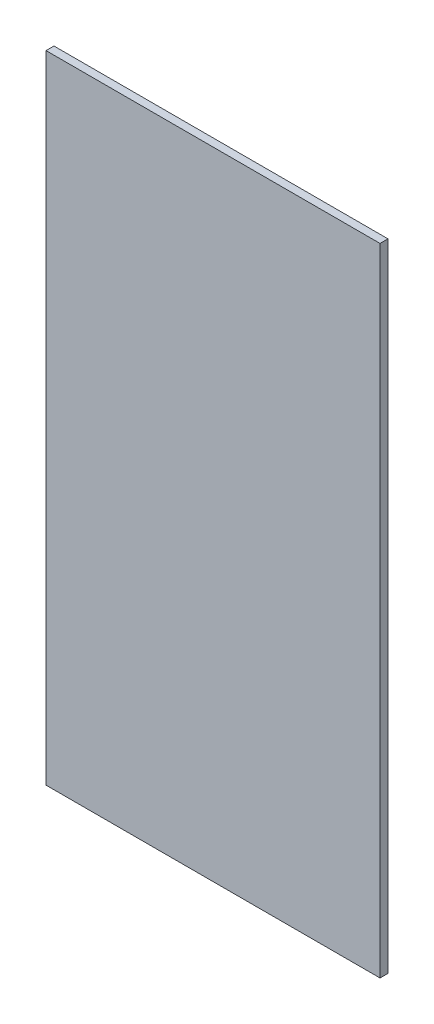
SolidWorks part; units mm, degrees
ref_plane "Front Plane" through (0, 0, 0) normal (0, 0, 1) x (1, 0, 0)
ref_plane "Top Plane" through (0, 0, 0) normal (0, 1, 0) x (1, 0, 0)
ref_plane "Right Plane" through (0, 0, 0) normal (1, 0, 0) x (0, 0, -1)
sketch "Sketch1" plane through (0, 0, 0) normal (0, 0, 1) x (1, 0, 0)
  line L1 (-1575, 3000) -> (1575, 3000)
  line L2 (-1575, 3000) -> (-1575, -3000)
  line L3 (-1575, -3000) -> (1575, -3000)
  line L4 (1575, 3000) -> (1575, -3000)
  line L5 (-1575, 3000) -> (1575, -3000) construction
  line L6 (-1575, -3000) -> (1575, 3000) construction
  point P0 (0, 0)
  point P6 (0, 0)
  point P7 (0, 0)
extrude "Boss-Extrude1" add sketch "Sketch1" along normal blind 75
